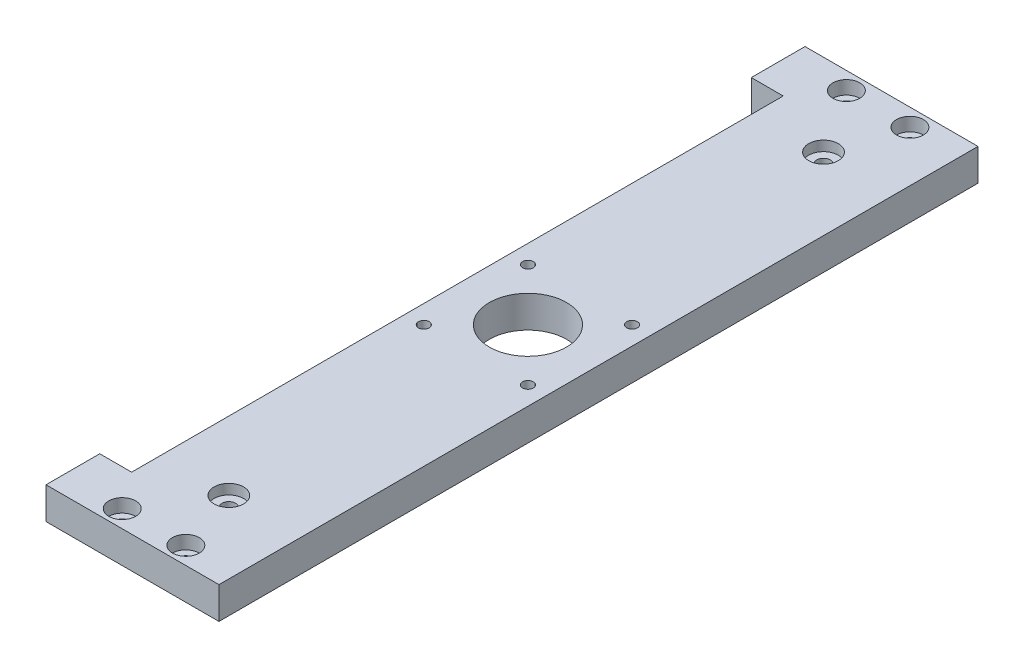
SolidWorks part; units mm, degrees
ref_plane "前视基准面" through (0, 0, 0) normal (0, 0, 1) x (1, 0, 0)
ref_plane "上视基准面" through (0, 0, 0) normal (0, 1, 0) x (1, 0, 0)
ref_plane "右视基准面" through (0, 0, 0) normal (1, 0, 0) x (0, 0, -1)
sketch "草图1" plane through (0, 0, 0) normal (0, 1, 0) x (1, 0, 0)
  line L1 (0, 0) -> (42, 0)
  line L2 (0, 0) -> (0, -226)
  line L3 (0, -226) -> (42, -226)
  line L4 (42, 0) -> (42, -226)
  dimension "D1" = 42
  dimension "D2" = 226
extrude "凸台-拉伸1" add sketch "草图1" along normal blind 9.5
sketch "草图2" plane through (0, 9.5, 0) normal (0, 1, 0) x (1, 0, 0)
  line L0 (0, -113) -> (42, -113) construction
  line L1 (0, 0) -> (0, -226) construction
  line L2 (42, -226) -> (42, 0) construction
  line L3 (21, 0) -> (21, -226) construction
  line L4 (42, 0) -> (0, 0) construction
  line L5 (0, -226) -> (42, -226) construction
  circle A0 centre (21, -113) radius 11.5
  dimension "D1" = 23
extrude "切除-拉伸1" cut sketch "草图2" against normal through all
sketch "草图3" plane through (0, 0, 0) normal (-1, 0, 0) x (0, 0, 1)
  line L0 (0, 0) -> (226, 0) construction
  line L1 (0, 9.5) -> (16, 9.5)
  line L2 (0, 9.5) -> (0, 0)
  line L3 (0, 0) -> (16, 0)
  line L4 (16, 9.5) -> (16, 0)
  line L5 (0, 9.5) -> (226, 9.5) construction
  line L6 (226, 0) -> (210, 0)
  line L7 (226, 0) -> (226, 9.5)
  line L8 (226, 9.5) -> (210, 9.5)
  line L9 (210, 0) -> (210, 9.5)
  dimension "D1" = 16
  dimension "D2" = 16
extrude "凸台-拉伸2" add sketch "草图3" along normal blind 9.5
sketch "草图4" plane through (0, 9.5, 0) normal (0, 1, 0) x (1, 0, 0)
  circle A0 centre (20.47, -201.5262) radius 4.4
  circle A1 centre (20.47, -24.4738) radius 4.4
  dimension "D1" = 8.8
extrude "切除-拉伸2" cut sketch "草图4" against normal blind 3
sketch "草图5" plane through (0, 0, 0) normal (0, -1, 0) x (1, 0, 0)
  circle A0 centre (5.5, 97.5) radius 1.6
  circle A1 centre (5.5, 128.5) radius 1.6
  circle A2 centre (36.5, 97.5) radius 1.6
  circle A3 centre (36.5, 128.5) radius 1.6
  dimension "D1" = 3.2
extrude "切除-拉伸3" cut sketch "草图5" against normal through all
sketch "草图6" plane through (0, 9.5, 0) normal (0, 1, 0) x (1, 0, 0)
  circle A0 centre (20.47, -201.5262) radius 2
  circle A1 centre (20.47, -24.4738) radius 2
  dimension "D1" = 4
extrude "切除-拉伸6" cut sketch "草图6" against normal through all
sketch "草图7" plane through (0, 9.5, 0) normal (0, 1, 0) x (1, 0, 0)
  line L0 (-9.5, -226) -> (42, -226) construction
  line L1 (0, -16) -> (0, -210) construction
  circle A0 centre (8, -220.8) radius 1.9
  circle A1 centre (26.9389, -220.8) radius 1.9
  dimension "D1" = 3.8
  dimension "D2" = 5.2
  dimension "D3" = 8
  dimension "D4" = 5.2
extrude "切除-拉伸7" cut sketch "草图7" against normal through all
sketch "草图9" plane through (0, 9.5, 0) normal (0, 1, 0) x (1, 0, 0)
  circle A0 centre (8, -220.8) radius 4
  circle A1 centre (26.9389, -220.8) radius 4
  dimension "D1" = 8
extrude "切除-拉伸8" cut sketch "草图9" against normal blind 4
sketch "草图10" plane through (0, 9.5, 0) normal (0, 1, 0) x (1, 0, 0)
  line L0 (0, -113) -> (42, -113) construction
  line L1 (0, -16) -> (0, -210) construction
  line L2 (42, -226) -> (42, 0) construction
ref_plane "基准面1" through (0, 0, 113) normal (0, 0, 1) x (1, 0, 0)
mirror "镜向1" about plane through (0, 0, 113) normal (0, 0, 1) of "切除-拉伸8", "切除-拉伸7"
